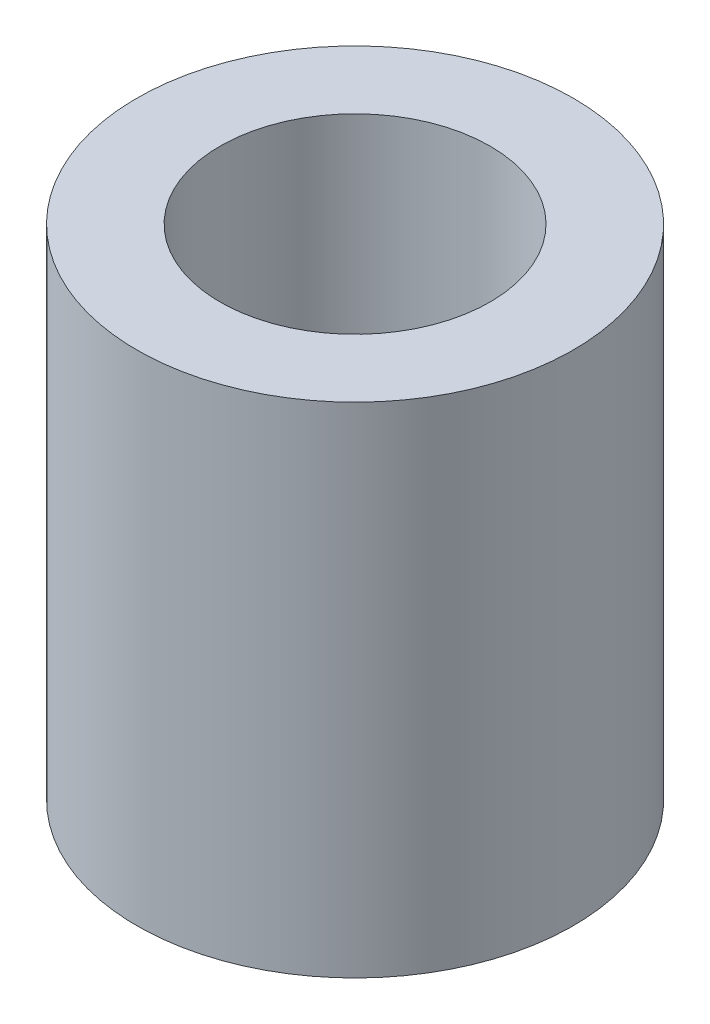
SolidWorks part; units mm, degrees
material "Polyurethane Foam Flexible"
ref_plane "Front Plane" through (0, 0, 0) normal (0, 0, 1) x (1, 0, 0)
ref_plane "Top Plane" through (0, 0, 0) normal (0, 1, 0) x (1, 0, 0)
ref_plane "Right Plane" through (0, 0, 0) normal (1, 0, 0) x (0, 0, -1)
sketch "Sketch1" plane through (0, 0, 0) normal (0, 1, 0) x (1, 0, 0)
  circle A0 centre (0, 0) radius 33.3375
  circle A1 centre (0, 0) radius 20.6375
extrude "Boss-Extrude1" add sketch "Sketch1" along normal blind 76.2
